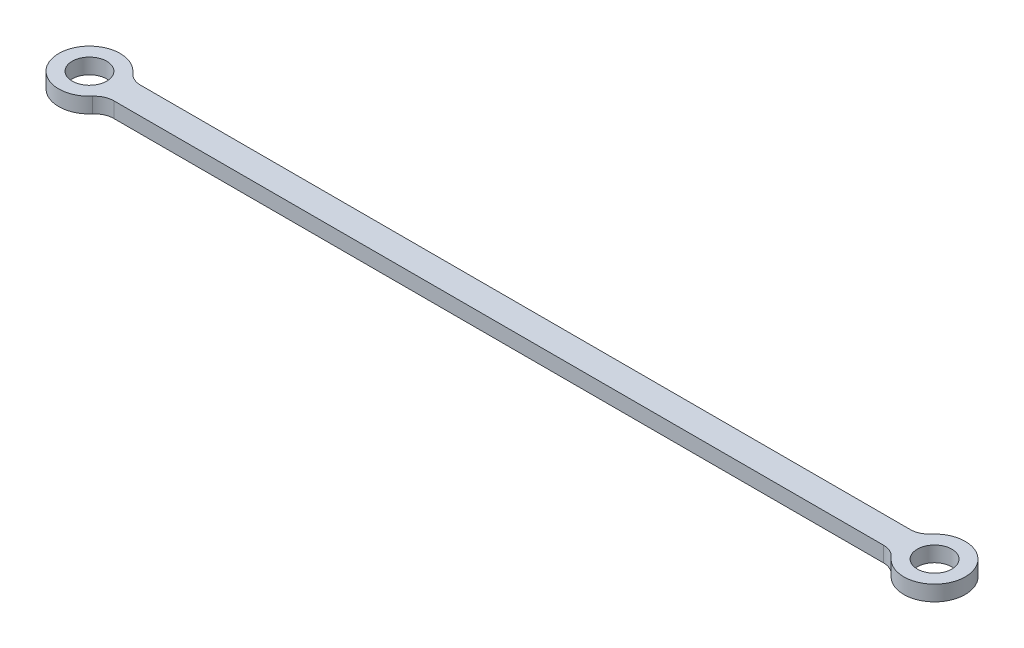
SolidWorks part; units mm, degrees
ref_plane "前视基准面" through (0, 0, 0) normal (0, 0, 1) x (1, 0, 0)
ref_plane "上视基准面" through (0, 0, 0) normal (0, 1, 0) x (1, 0, 0)
ref_plane "右视基准面" through (0, 0, 0) normal (1, 0, 0) x (0, 0, -1)
sketch "草图1" plane through (0, 0, 0) normal (0, 1, 0) x (1, 0, 0)
  line L0 (-100.1638, 3.5) -> (100.1638, 3.5)
  line L1 (100.1638, -3.5) -> (-100.1638, -3.5)
  line L2 (0, 0) -> (69.7116, 0) construction
  line L3 (0, 0) -> (0, 43.1251) construction
  arc A0 (103.947, 5.2308) -> (103.947, -5.2308) centre (110, 0) cw
  arc A1 (-103.947, 5.2308) -> (-103.947, -5.2308) centre (-110, 0) ccw
  arc A2 (-100.1638, -3.5) -> (-103.947, -5.2308) centre (-100.1638, -8.5) ccw
  arc A3 (100.1638, -3.5) -> (103.947, -5.2308) centre (100.1638, -8.5) cw
  arc A4 (100.1638, 3.5) -> (103.947, 5.2308) centre (100.1638, 8.5) ccw
  arc A5 (-100.1638, 3.5) -> (-103.947, 5.2308) centre (-100.1638, 8.5) cw
  circle A6 centre (110, 0) radius 4.5
  circle A7 centre (-110, 0) radius 4.5
  point P11 (0, 0)
  dimension "D1" = 5
  dimension "D3" = 9
  dimension "D4" = 8
  dimension "D2" = 220
  dimension "D5" = 7
extrude "凸台-拉伸1" add sketch "草图1" along normal blind 4
